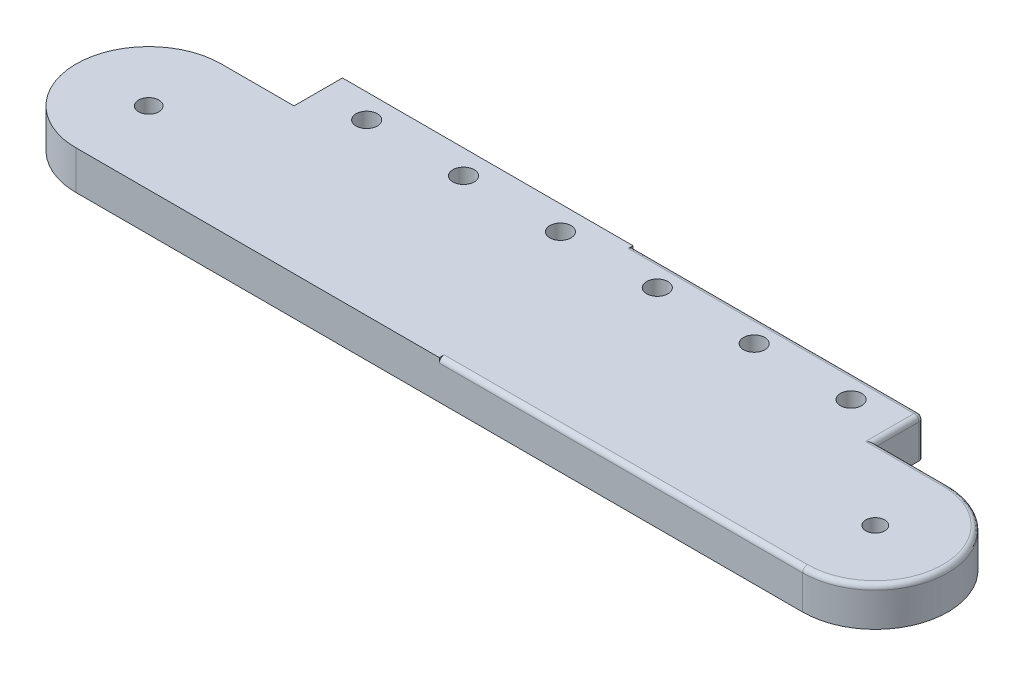
SolidWorks part; units mm, degrees
ref_plane "Front Plane" through (0, 0, 0) normal (0, 0, 1) x (1, 0, 0)
ref_plane "Top Plane" through (0, 0, 0) normal (0, 1, 0) x (1, 0, 0)
ref_plane "Right Plane" through (0, 0, 0) normal (1, 0, 0) x (0, 0, -1)
sketch "Sketch2" plane through (0, 0, 0) normal (0, 1, 0) x (1, 0, 0)
  line L0 (0, 0) -> (30, 0)
  line L1 (0, 0) -> (0, 15) construction
  line L2 (0, -55) -> (0, 55) construction
  line L3 (30, 0) -> (30, 15) construction
  line L4 (0, 15) -> (30, 15) construction
  line L5 (30, 15) -> (30, 20)
  line L6 (30, 20) -> (0, 20)
  line L7 (0, 20) -> (0, 15)
  line L8 (0, 7.5) -> (-7.5, 7.5) construction
  line L9 (30, 7.5) -> (37.5, 7.5) construction
  line L10 (-55, 0) -> (55, 0) construction
  line L11 (-7.5, 15) -> (0, 15)
  line L12 (30, 15) -> (37.5, 15)
  line L13 (37.5, 0) -> (-7.5, 0)
  ellipse E0 centre (-7.5, 7.5) end of major axis (0, 7.5) minor radius 7.5 (-7.5, 0) -> (-7.5, 15) cw
  ellipse E1 centre (37.5, 7.5) end of major axis (37.5, 0) minor radius 7.5 (37.5, 0) -> (37.5, 15) ccw
  point P13 (0, 0)
  dimension "D1" = 30
  dimension "D2" = 5
  dimension "D3" = 15
extrude "Boss-Extrude1" add sketch "Sketch2" along normal blind 4 contours L13 E1 L12 L5 L6 L7 L11 E0 L0
sketch "Sketch3" plane through (0, 0, 0) normal (0, 1, 0) x (1, 0, 0)
  line L0 (30, 20) -> (30, 17.5) construction
  line L1 (30, 15) -> (30, 20) construction
  line L2 (30, 17.5) -> (15, 17.5) construction
  circle A0 centre (15, 17.5) radius 1.1
  point P7 (15.2665, 17.5)
  dimension "D1" = 2.2
  dimension "D2" = 15
extrude "Cut-Extrude2" cut sketch "Sketch3" against normal through all both and the other way through all
sketch "Sketch4" plane through (0, 0, 0) normal (0, 1, 0) x (1, 0, 0)
  line L0 (0, 0) -> (0, 7.5) construction
  line L1 (0, -55) -> (0, 55) construction
  line L2 (0, 7.5) -> (-7.5, 7.5) construction
  line L3 (30, 15) -> (30, 7.5) construction
  line L4 (30, 7.5) -> (37.5, 7.5) construction
  circle A0 centre (-7.5, 7.5) radius 0.99
  circle A1 centre (37.5, 7.5) radius 0.98
extrude "Cut-Extrude3" cut sketch "Sketch4" against normal through all both and the other way through all
fillet "Fillet1" radius 0.5 5 edges at (33.75, 4, -15) (45, 4, -7.5) (-3.75, 4, -15) (-15, 4, -7.5) (15, 4, 0)
fillet "Fillet2" radius 0.5 1 edges at (15, 4, -20)
fillet "Fillet4" radius 0.5 3 edges at (30, 1.75, -20) (30, 3.8536, -19.8536) (30, 4, -17)
sketch "Sketch5" plane through (0, 0, 0) normal (0, 1, 0) x (1, 0, 0)
  line L1 (0, 0) -> (-16.045, 0)
  line L2 (0, 0) -> (0, 15)
  line L3 (0, 15) -> (-16.045, 15)
  line L4 (-16.045, 0) -> (-16.045, 15)
extrude "Cut-Extrude4" cut sketch "Sketch5" along normal blind 10
sketch "Sketch6" plane through (0, 0, 0) normal (0, 1, 0) x (1, 0, 0)
  line L0 (0, 0) -> (-37.5, 0)
  line L1 (0, 20) -> (-30, 20)
  line L2 (-30, 20) -> (-30, 15)
  line L3 (-37.5, 0) -> (-37.5, 15) construction
  line L4 (-37.5, 15) -> (-30, 15)
  line L5 (-37.5, 7.5) -> (-45, 7.5) construction
  line L6 (0, 20) -> (0, 0)
  circle A0 centre (-37.5, 7.5) radius 1.05
  ellipse E0 centre (-37.5, 7.5) end of major axis (-37.5, 0) minor radius 7.5 (-37.5, 15) -> (-37.5, 0) ccw
extrude "Boss-Extrude2" add sketch "Sketch6" along normal blind 4
fillet "Fillet5" [suppressed] radius 0.5
pattern_linear "LPattern1" [suppressed] count 2 spacing 2 count 5 spacing 8
scale "Scale1" [suppressed]
sketch "Sketch7" [suppressed] plane through (0, 0, -20) normal (0, 0, -1) x (-1, 0, 0)
  line L0 (-29.5, -2.5) -> (29.5, -2.5) construction
  line L1 (29.5, 3.5) -> (0.5, 3.5) construction
  line L2 (-29.5, -2.5) -> (29.5, -2.5)
  line L3 (29.5, 3.5) -> (0.5, 3.5)
  line L4 (0, 0.5) -> (-29.5, 0.5) construction
  line L5 (29.5, -2.5) -> (29.5, 3.5) construction
  circle A1 centre (23.5, 0.5) radius 2.2
  point P3 (0, 0)
  dimension "D1" = 4.4
  dimension "D2" = 6
extrude "Cut-Extrude5" [suppressed] cut sketch "Sketch7" against normal blind 6 and the other way through all contours L4 A1 | A1 L4
pattern_linear "LPattern2" [suppressed] count 12 spacing 5
pattern_linear "LPattern3" count 5 spacing 10 along (-1, 0, 0) count 5 spacing 10 along (1, 0, 0) of "Cut-Extrude2"
